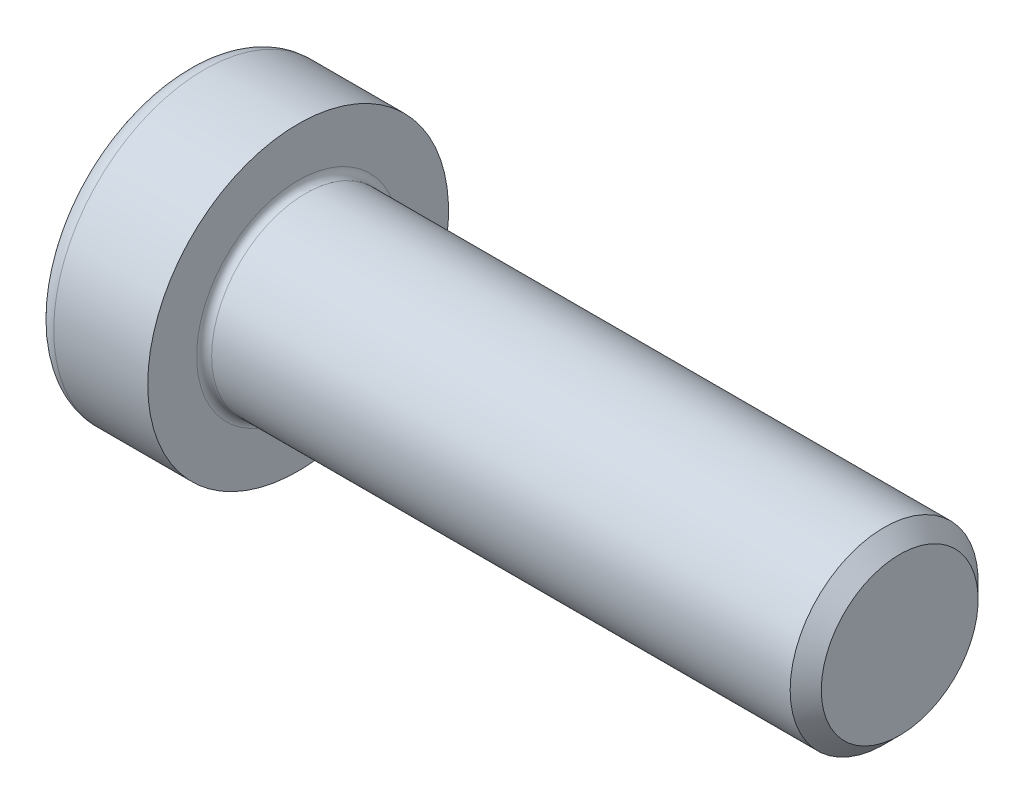
SolidWorks part; units mm, degrees
revolve "Base-Revolve" add sketch "BodySke"
sketch "BodySke" plane through (0, 0, 0) normal (0, 0, 1) x (1, 0, 0)
  line L0 (0, 0) -> (0, 8)
  line L1 (0, 8) -> (6, 8)
  line L2 (6, 8) -> (6, 5)
  line L3 (6, 5) -> (37.172, 5)
  line L4 (38, 4.172) -> (38, 0)
  line L5 (38, 0) -> (0, 0)
  line L6 (-31.75, 0) -> (127, 0) construction
  line L8 (38, 4.172) -> (37.172, 5)
  line L10 (38, -4.172) -> (37.172, -5) construction
  line L11 (7.5, 4.525) -> (7.5, -1.825) construction
  line L12 (12, 4.525) -> (12, -1.825) construction
  line L13 (-22, 4.525) -> (-22, -1.825) construction
  dimension "Head_ht" = 6
  dimension "Length" = 32
  dimension "Body_ch_ang" = 45
  dimension "Diameter" = 10
  dimension "Minor_dia" = 8.344
  dimension "Advance" = 1.5
  dimension "Thread_nom" = 26
  dimension "Thread_length" = 60
  dimension "Head_dia" = 16
cosmetic thread "ThreadCosmetic"
fillet "Fillet1" radius 0.4 1 edges at (6, 0, 5)
fillet "Fillet2" radius 1 1 edges at (0, 0, 8)
material "AISI 316 Нержавеющая сталь, лист (SS)"
ref_plane "Plane1" through (0, 0, 0) normal (0, 0, 1) x (1, 0, 0)
ref_plane "Plane2" through (0, 0, 0) normal (0, 1, 0) x (1, 0, 0)
ref_plane "Plane3" through (0, 0, 0) normal (1, 0, 0) x (0, 0, -1)
other "Configuration Table"
sketch "Sketch2" plane through (0, 0, 0) normal (0, 0, 1) x (1, 0, 0)
  line L0 (0, 3.5) -> (4.5, 3.5)
  line L1 (4.5, 3.5) -> (6.5207, 0)
  line L2 (-31.75, 0) -> (127, 0) construction
  line L3 (6.5207, 0) -> (0, 0)
  line L4 (0, 0) -> (0, 3.5)
  line L6 (0, 0) -> (47.625, 0) construction
  dimension "D1" = 3.5
  dimension "D2" = 60
  dimension "Depth" = 4.5
revolve "Hex-PreBroach" cut sketch "Sketch2" angle 360 about L6
sketch "Sketch3" plane through (0, 0, 0) normal (-1, 0, 0) x (0, 0.5, 0.866)
  line L0 (2.0207, 3.5) -> (-2.0207, 3.5)
  line L1 (-2.0207, 3.5) -> (-4.0415, 0)
  line L2 (2.0207, 3.5) -> (4.0415, 0)
  line L3 (2.0207, -3.5) -> (4.0415, 0)
  line L4 (2.0207, -3.5) -> (-2.0207, -3.5)
  line L5 (-2.0207, -3.5) -> (-4.0415, 0)
  dimension "D1" = 3.5
  dimension "D2" = 3.5
  dimension "Hex_size" = 7
extrude "Hex" cut sketch "Sketch3" against normal blind 4.5
sketch "ThdSchSke" plane through (0, 0, 0) normal (0, 0, 1) x (1, 0, 0)
  line L0 (12, -4.172) -> (11.4202, -5)
  line L1 (12, -4.172) -> (12.5798, -5)
  line L2 (12.5798, -5) -> (12.5798, -6.25)
  line L3 (-3.175, 0) -> (5.1513, 0) construction
  line L4 (0, 7) -> (0, -7) construction
  line L5 (12.5798, -6.25) -> (11.4202, -6.25)
  line L6 (11.4202, -6.25) -> (11.4202, -5)
  dimension "Thread_minor" = 8.344
  dimension "Diameter" = 10
  dimension "Start" = 12
revolve "ThreadSchematic" [suppressed] cut sketch "ThdSchSke" angle 360 about L3
pattern_linear "ThdSchPat" [suppressed]
equation "\"D2@Sketch3\" = \"Hex_size@Sketch3\" / 2"
equation "\"D1@Sketch3\" = \"Hex_size@Sketch3\" / 2"
equation "\"D1@Sketch2\" = \"Hex_size@Sketch3\" / 2"
equation "\"Thread_minor@ThreadCosmetic\"  =  \"Minor_dia@BodySke\""
equation "\"Depth@Sketch2\" =  \"Key_eng@Hex\""
equation "\"Thread_length@ThreadCosmetic\" = ((sgn( (\"Length@BodySke\" - \"Advance@BodySke\" * 3.0) - \"Thread_nom@BodySke\" )-1)*( (\"Length@BodySke\" - \"Advance@BodySke\" * 3.0) - \"Thread_nom@BodySke\" ))/-2+ \"Thread_nom@BodySke\""
equation "\"Thread_minor@ThdSchSke\" = \"Minor_dia@BodySke\""
equation "\"Diameter@ThdSchSke\" = \"Diameter@BodySke\""
equation "\"Overcut@ThdSchSke\" = \"Diameter@BodySke\" * 1.25"
equation "\"Start@ThdSchSke\" = \"Head_ht@BodySke\" + \"Length@BodySke\" - \"Thread_length@ThreadCosmetic\"  '---Non-countersunk---"
equation "\"Num_threads@ThdSchPat\" = int( \"Thread_length@ThreadCosmetic\" / \"Advance@BodySke\" + 0.999 )  + 1"
equation "\"Advance@ThdSchPat\" = \"Thread_length@ThreadCosmetic\" /  (\"Num_threads@ThdSchPat\" - 1) 'relax it"
equation "\"Num_threads@ThdSchPat\" = \"Num_threads@ThdSchPat\" - sgn( \"Num_threads@ThdSchPat\" - 1) '---chamfered tips only---"
